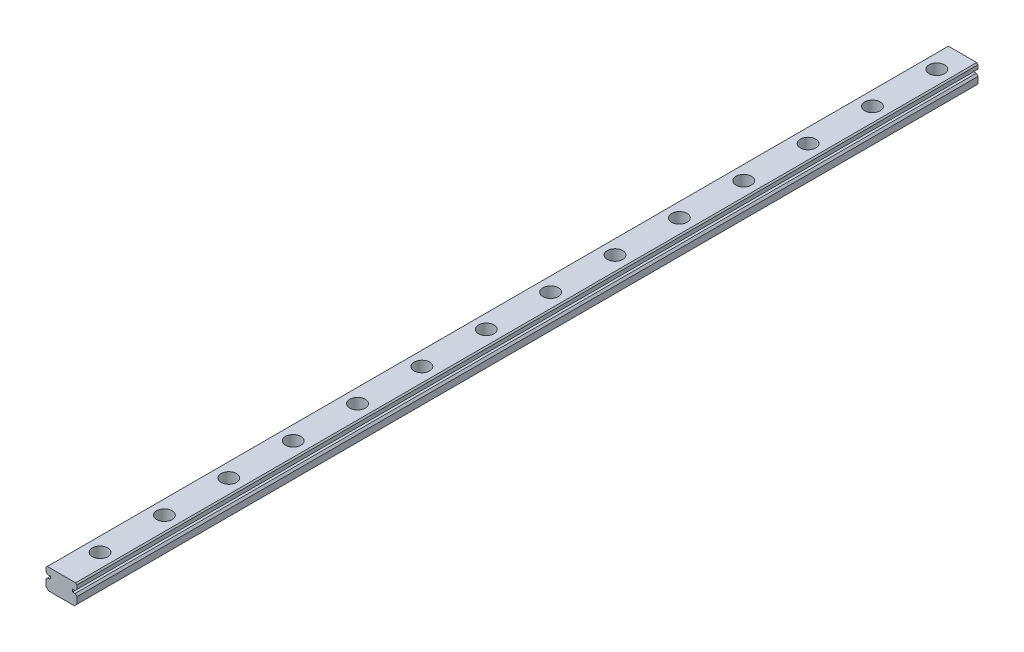
SolidWorks part; units mm, degrees
material "AISI 1020 Steel, Cold Rolled"
ref_plane "Front Plane" through (0, 0, 0) normal (0, 0, 1) x (1, 0, 0)
ref_plane "Top Plane" through (0, 0, 0) normal (0, 1, 0) x (1, 0, 0)
ref_plane "Right Plane" through (0, 0, 0) normal (1, 0, 0) x (0, 0, -1)
ref_plane "RailEndPlane" through (0, 0, 350) normal (0, 0, 1) x (1, 0, 0)
sketch "MainProfile" plane through (0, 0, 0) normal (0, 0, 1) x (1, 0, 0)
  line L0 (0, 0) -> (0, 3.5858)
  line L1 (0, 8) -> (12, 8)
  line L2 (12, 8) -> (12, 6)
  line L3 (12, 0) -> (0, 0)
  line L4 (6, 8) -> (6, -2.3077) construction
  line L5 (0, 6) -> (0.7071, 5.2929)
  line L6 (0.7071, 5.2929) -> (1.7071, 5.2929)
  line L7 (1.7071, 5.2929) -> (1.7071, 4.2929)
  line L8 (1.7071, 4.2929) -> (0.7071, 4.2929)
  line L9 (0.7071, 4.2929) -> (0, 3.5858)
  line L10 (0, 6) -> (0, 8)
  line L11 (11.2929, 4.2929) -> (12, 3.5858)
  line L12 (10.2929, 4.2929) -> (11.2929, 4.2929)
  line L13 (10.2929, 5.2929) -> (10.2929, 4.2929)
  line L14 (11.2929, 5.2929) -> (10.2929, 5.2929)
  line L15 (12, 6) -> (11.2929, 5.2929)
  line L16 (12, 3.5858) -> (12, 0)
  dimension "D1" = 8
  dimension "D2" = 12
  dimension "D3" = 270
  dimension "D4" = 1
  dimension "D5" = 2
  dimension "D6" = 2.7071
extrude "Main Extrusion" add sketch "MainProfile" along normal up to surface (350 mm away) up to plane "RailEndPlane"
sketch "First Hole Position" plane through (0, 0, 0) normal (0, 1, 0) x (1, 0, 0)
  point P0 (6, -10)
  dimension "D1" = 10
  dimension "D2" = 6
hole_wizard "Mounting Hole Master" positions "Sketch2" profile "Sketch3" legacy
sketch "Sketch2" plane through (0, 8, 0) normal (0, 1, 0) x (1, 0, 0)
  point P0 (6, -10)
sketch "Sketch3" plane through (6, 8, 10) normal (1, 0, 0) x (0, 0, 1)
  line L0 (0, 0) -> (0, 9.9216)
  line L1 (0, 9.9216) -> (1.75, 9.9216)
  line L2 (1.75, 9.9216) -> (1.75, 4.5)
  line L3 (1.75, 4.5) -> (3, 4.5)
  line L4 (3, 4.5) -> (3, 0)
  line L5 (3, 0) -> (0, 0)
  line L6 (0, 110) -> (0, -10) construction
  dimension "Diameter" = 3.5
  dimension "Depth" = 10
  dimension "C-Bore Diameter" = 6
  dimension "C-Bore Depth" = 4.5
pattern_linear "Mounting Holes Pattern" count 14 spacing 25 along (0, 0, 1) of "Mounting Hole Master"
chamfer "Rail Top Chamfer" distance 0.5 angle 45 2 edges at (0, 8, 175) (12, 8, 175)
chamfer "Rail Bottom Chamfer" distance 1 angle 45 2 edges at (0, 0, 175) (12, 0, 175)
